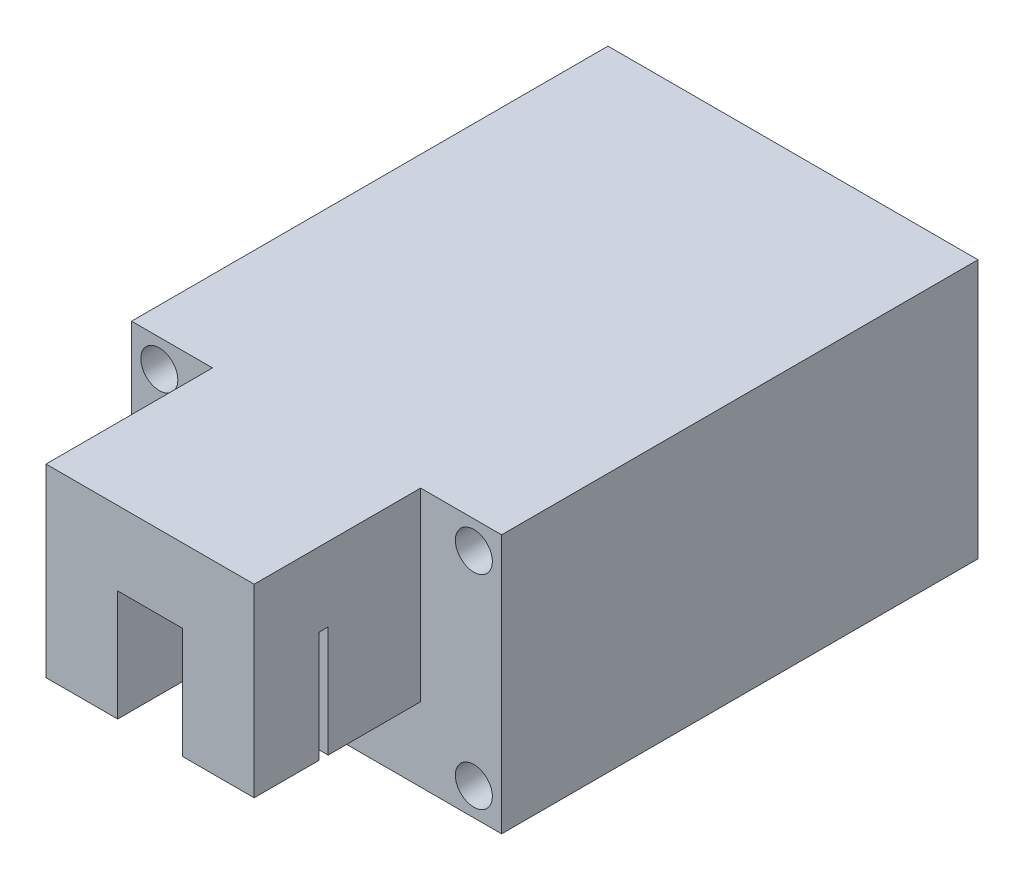
SolidWorks part; units mm, degrees
ref_plane "前视基准面" through (0, 0, 0) normal (0, 0, 1) x (1, 0, 0)
ref_plane "上视基准面" through (0, 0, 0) normal (0, 1, 0) x (1, 0, 0)
ref_plane "右视基准面" through (0, 0, 0) normal (1, 0, 0) x (0, 0, -1)
sketch "草图1" plane through (0, 0, 0) normal (0, 0, 1) x (1, 0, 0)
  line L1 (-20, -14) -> (20, -14)
  line L2 (-20, -14) -> (-20, 14)
  line L3 (-20, 14) -> (20, 14)
  line L4 (20, -14) -> (20, 14)
  line L5 (-20, -14) -> (20, 14) construction
  line L6 (-20, 14) -> (20, -14) construction
  circle A0 centre (-17, 11) radius 2
  circle A1 centre (17, 11) radius 2
  circle A2 centre (-17, -11) radius 2
  circle A3 centre (17, -11) radius 2
  point P0 (0, 0)
  dimension "D3" = 4
  dimension "D4" = 4
  dimension "D5" = 4
  dimension "D6" = 4
  dimension "D7" = 3
  dimension "D8" = 3
  dimension "D9" = 3
  dimension "D10" = 3
  dimension "D11" = 3
  dimension "D12" = 3
  dimension "D13" = 3
  dimension "D14" = 3
  dimension "D1" = 28
  dimension "D2" = 40
extrude "凸台-拉伸1" add sketch "草图1" along normal blind 51.5
sketch "草图2" plane through (0, 0, 51.5) normal (0, 0, 1) x (1, 0, 0)
  line L0 (20, 14) -> (-20, 14) construction
  line L1 (-11.25, 14) -> (11.25, 14)
  line L2 (-11.25, 14) -> (-11.25, -6)
  line L3 (-11.25, -6) -> (11.25, -6)
  line L4 (11.25, 14) -> (11.25, -6)
  dimension "D1" = 22.5
  dimension "D2" = 20
extrude "凸台-拉伸2" add sketch "草图2" along normal blind 18
sketch "草图3" plane through (0, -6, 0) normal (0, -1, 0) x (1, 0, 0)
  line L0 (-20, 51.5) -> (20, 51.5) construction
  line L1 (-6.75, 51.5) -> (6.75, 51.5)
  line L2 (-6.75, 51.5) -> (-6.75, 58.5)
  line L3 (-6.75, 58.5) -> (6.75, 58.5)
  line L4 (6.75, 51.5) -> (6.75, 58.5)
  line L5 (-11.25, 69.5) -> (-11.25, 51.5) construction
  dimension "D1" = 7
  dimension "D2" = 13.5
  dimension "D3" = 4.5
extrude "切除-拉伸1" cut sketch "草图3" against normal blind 12
sketch "草图4" plane through (0, -6, 0) normal (0, -1, 0) x (1, 0, 0)
  line L0 (-11.25, 69.5) -> (-11.25, 51.5) construction
  line L1 (-11.25, 61.5) -> (11.25, 61.5)
  line L2 (-11.25, 61.5) -> (-11.25, 62.5)
  line L3 (-11.25, 62.5) -> (11.25, 62.5)
  line L4 (11.25, 61.5) -> (11.25, 62.5)
  line L5 (11.25, 69.5) -> (11.25, 51.5) construction
  line L6 (-11.25, 51.5) -> (-6.75, 51.5) construction
  dimension "D1" = 10
  dimension "D2" = 1
extrude "切除-拉伸2" cut sketch "草图4" against normal blind 12
sketch "草图5" plane through (0, 0, 69.5) normal (0, 0, 1) x (1, 0, 0)
  line L0 (-11.25, -6) -> (11.25, -6) construction
  line L1 (-3.5, -6) -> (3.5, -6)
  line L2 (-3.5, -6) -> (-3.5, 6)
  line L3 (-3.5, 6) -> (3.5, 6)
  line L4 (3.5, -6) -> (3.5, 6)
  line L5 (-11.25, 14) -> (-11.25, -6) construction
  dimension "D1" = 12
  dimension "D2" = 7
  dimension "D3" = 7.75
extrude "切除-拉伸3" cut sketch "草图5" against normal blind 7
sketch "草图6" plane through (0, 0, 0) normal (0, 0, -1) x (-1, 0, 0)
  line L0 (20, 0) -> (-20, 0)
  line L1 (20, 14) -> (20, -14) construction
  line L2 (-20, -14) -> (-20, 14) construction
